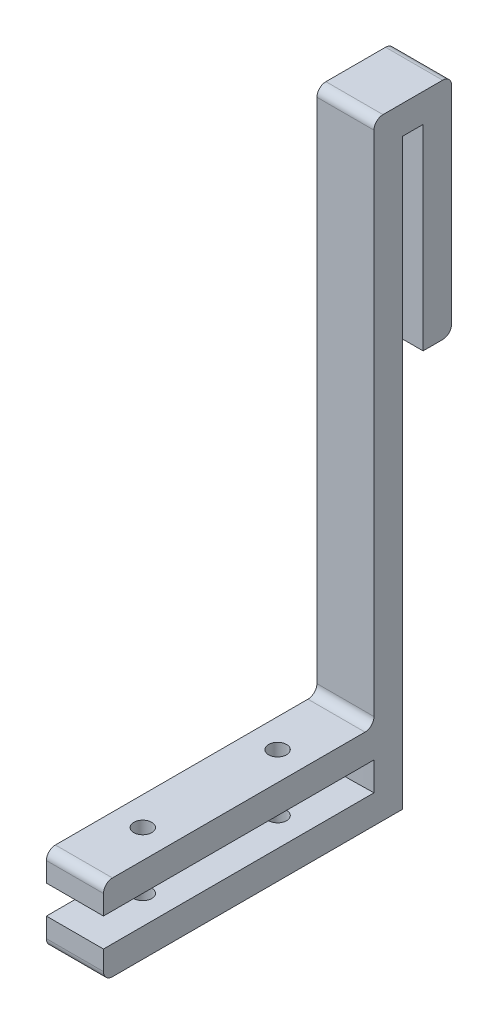
SolidWorks part; units mm, degrees
ref_plane "Front Plane" through (0, 0, 0) normal (0, 0, 1) x (1, 0, 0)
ref_plane "Top Plane" through (0, 0, 0) normal (0, 1, 0) x (1, 0, 0)
ref_plane "Right Plane" through (0, 0, 0) normal (1, 0, 0) x (0, 0, -1)
sketch "Sketch1" plane through (0, 0, 0) normal (0, 1, 0) x (1, 0, 0)
  line L1 (0, 0) -> (12.7, 0)
  line L2 (0, 0) -> (0, 66.548)
  line L3 (0, 66.548) -> (12.7, 66.548)
  line L4 (12.7, 0) -> (12.7, 66.548)
  dimension "D1" = 66.548
  dimension "D2" = 12.7
extrude "Boss-Extrude1" add sketch "Sketch1" along normal blind 6.35
sketch "Sketch2" plane through (0, 6.35, 0) normal (0, 1, 0) x (1, 0, 0)
  line L0 (12.7, 0) -> (12.7, 66.548) construction
  line L1 (0, 66.548) -> (12.7, 66.548)
  line L2 (0, 66.548) -> (0, 60.198)
  line L3 (0, 60.198) -> (12.7, 60.198)
  line L4 (12.7, 66.548) -> (12.7, 60.198)
  dimension "D1" = 6.35
extrude "Boss-Extrude2" add sketch "Sketch2" along normal blind 6.35
sketch "Sketch3" plane through (0, 12.7, 0) normal (0, 1, 0) x (1, 0, 0)
  line L1 (0, 66.548) -> (12.7, 66.548)
  line L2 (0, 66.548) -> (0, 0)
  line L3 (0, 0) -> (12.7, 0)
  line L4 (12.7, 66.548) -> (12.7, 0)
extrude "Boss-Extrude3" add sketch "Sketch3" along normal blind 6.35
sketch "Sketch4" plane through (0, 19.05, 0) normal (0, 1, 0) x (1, 0, 0)
  line L0 (12.7, 0) -> (12.7, 66.548) construction
  line L1 (0, 66.548) -> (12.7, 66.548)
  line L2 (0, 66.548) -> (0, 60.198)
  line L3 (0, 60.198) -> (12.7, 60.198)
  line L4 (12.7, 66.548) -> (12.7, 60.198)
  dimension "D1" = 6.35
extrude "Boss-Extrude4" add sketch "Sketch4" along normal blind 117
sketch "Sketch5" plane through (0, 0, -66.548) normal (0, 0, -1) x (-1, 0, 0)
  line L0 (0, 136.05) -> (0, 0) construction
  line L1 (-12.7, 136.05) -> (0, 136.05)
  line L2 (-12.7, 136.05) -> (-12.7, 129.7)
  line L3 (-12.7, 129.7) -> (0, 129.7)
  line L4 (0, 136.05) -> (0, 129.7)
  dimension "D1" = 6.35
extrude "Boss-Extrude5" add sketch "Sketch5" along normal blind 4.572
sketch "Sketch6" plane through (0, 0, -71.12) normal (0, 0, -1) x (-1, 0, 0)
  line L0 (0, 136.05) -> (-12.7, 136.05) construction
  line L1 (-12.7, 136.05) -> (0, 136.05)
  line L2 (-12.7, 136.05) -> (-12.7, 86.05)
  line L3 (-12.7, 86.05) -> (0, 86.05)
  line L4 (0, 136.05) -> (0, 86.05)
  point P9 (-6.35, 86.05)
  dimension "D1" = 50
extrude "Boss-Extrude6" add sketch "Sketch6" along normal blind 6.35
sketch "Sketch7" plane through (0, 6.35, 0) normal (0, 1, 0) x (1, 0, 0)
  line L0 (12.7, 60.198) -> (0, 60.198)
  arc A0 (12.7, 60.198) -> (0, 60.198) centre (6.35, 282.3573) cw
  dimension "D1" = 222.25
extrude "Boss-Extrude7" add sketch "Sketch7" along normal blind 6.35
ref_plane "Plane1" through (12.7, 19.05, -60.198) normal (0, 0, -1) x (-1, 0, 0)
sketch "Sketch9" plane through (0, 19.05, 0) normal (0, 1, 0) x (1, 0, 0)
  line L0 (6.35, 60.198) -> (6.35, 0) construction
  line L1 (0, 60.198) -> (12.7, 60.198) construction
  line L2 (0, 0) -> (12.7, 0) construction
  line L3 (0, 30.099) -> (12.7, 30.099) construction
  line L4 (12.7, 0) -> (12.7, 60.198) construction
  circle A0 centre (6.35, 45.099) radius 2
  circle A1 centre (6.35, 15.099) radius 2
  point P13 (6.35, 30.099)
  dimension "D2" = 4
  dimension "D1" = 30
extrude "Cut-Extrude1" cut sketch "Sketch9" against normal through all
fillet "Fillet1" radius 2 5 edges at (6.35, 0, 0) (6.35, 19.05, 0) (6.35, 86.05, -77.47) (6.35, 136.05, -77.47) (6.35, 136.05, -60.198)
fillet "Fillet2" radius 2 1 edges at (6.35, 19.05, -60.198)
